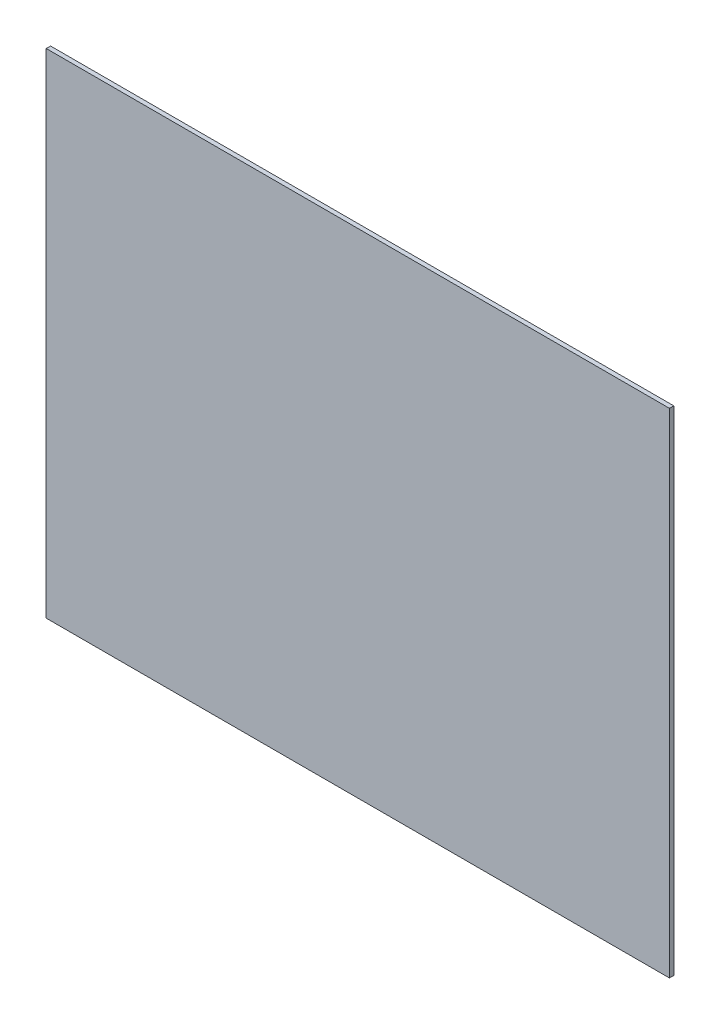
SolidWorks part; units mm, degrees
ref_plane "Front Plane" through (0, 0, 0) normal (0, 0, 1) x (1, 0, 0)
ref_plane "Top Plane" through (0, 0, 0) normal (0, 1, 0) x (1, 0, 0)
ref_plane "Right Plane" through (0, 0, 0) normal (1, 0, 0) x (0, 0, -1)
sketch "Sketch1" plane through (0, 0, 0) normal (0, 0, 1) x (1, 0, 0)
  line L1 (0, 0) -> (457.2, 0)
  line L2 (0, 0) -> (0, 361.95)
  line L3 (0, 361.95) -> (457.2, 361.95)
  line L4 (457.2, 0) -> (457.2, 361.95)
  dimension "D1" = 457.2
  dimension "D2" = 361.95
extrude "Boss-Extrude1" add sketch "Sketch1" along normal blind 3.175
